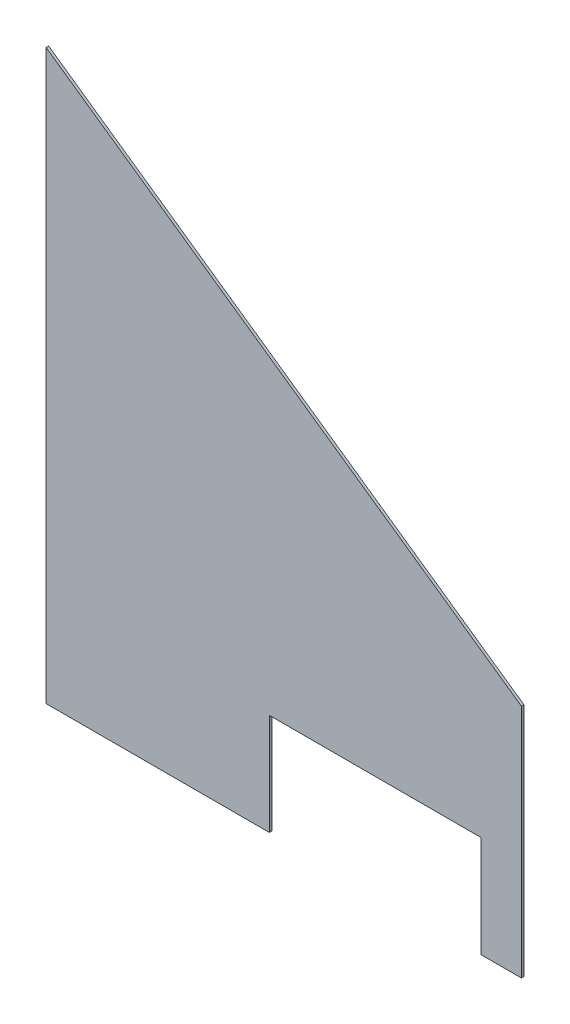
SolidWorks part; units mm, degrees
ref_plane "Front Plane" through (0, 0, 0) normal (0, 0, 1) x (1, 0, 0)
ref_plane "Top Plane" through (0, 0, 0) normal (0, 1, 0) x (1, 0, 0)
ref_plane "Right Plane" through (0, 0, 0) normal (1, 0, 0) x (0, 0, -1)
sketch "Sketch1" plane through (0, 0, 0) normal (0, 0, 1) x (1, 0, 0)
  line L0 (-32.9157, -20.5832) -> (246.4843, -20.5832)
  line L1 (-32.9157, -20.5832) -> (-32.9157, 690.6168)
  line L2 (-32.9157, 690.6168) -> (473.2307, 336.2093)
  line L3 (473.2307, 336.2093) -> (561.9523, 274.0858)
  line L4 (561.9523, 274.0858) -> (561.9523, -20.5832)
  line L5 (246.4843, -20.5832) -> (246.4843, 106.4168)
  line L6 (246.4843, 106.4168) -> (511.1523, 106.4168)
  line L7 (511.1523, 106.4168) -> (511.1523, -20.5832)
  line L8 (511.1523, -20.5832) -> (561.9523, -20.5832)
  dimension "D1" = 594.868
  dimension "D2" = 711.2
  dimension "D3" = 55
  dimension "D5" = 180
  dimension "D6" = 127
  dimension "D7" = 279.4
  dimension "D8" = 50.8
extrude "Boss-Extrude1" add sketch "Sketch1" along normal blind 3.175
